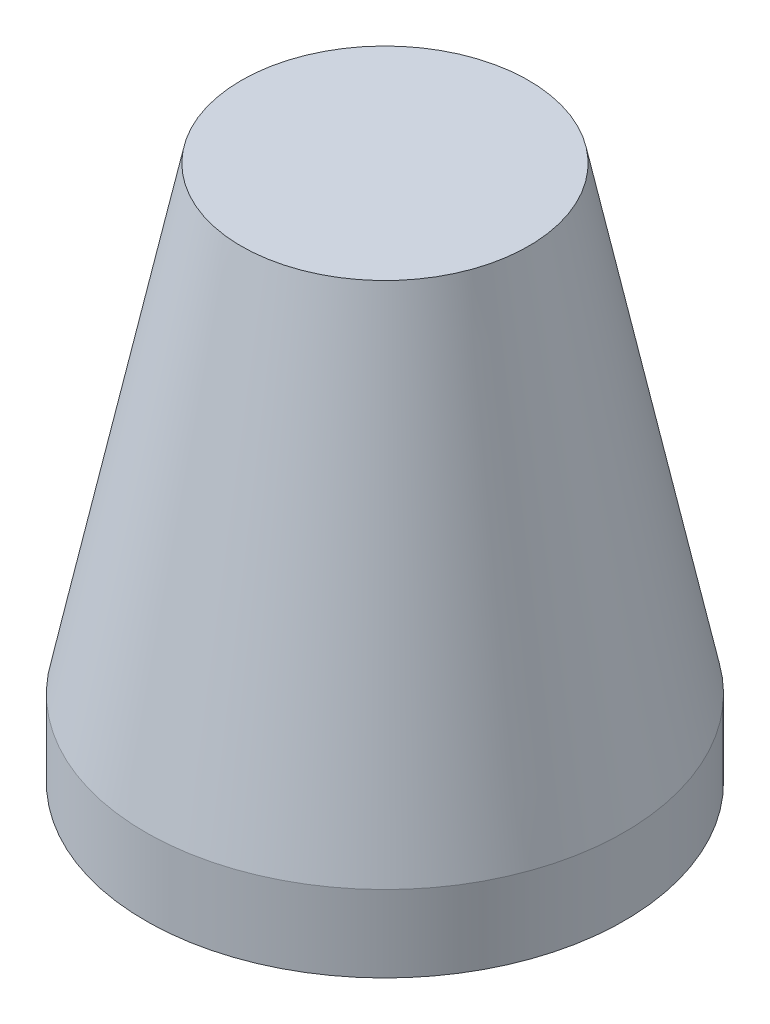
SolidWorks part; units mm, degrees
ref_plane "前视基准面" through (0, 0, 0) normal (0, 0, 1) x (1, 0, 0)
ref_plane "上视基准面" through (0, 0, 0) normal (0, 1, 0) x (1, 0, 0)
ref_plane "右视基准面" through (0, 0, 0) normal (1, 0, 0) x (0, 0, -1)
other "Configuration Table"
sketch "草图1" plane through (0, 0, 0) normal (0, 0, 1) x (1, 0, 0)
  line L0 (0, 56) -> (0, 0)
  line L1 (0, 0) -> (-25, 0)
  line L2 (-25, 0) -> (-25, 8)
  line L3 (-25, 8) -> (-15, 56)
  line L4 (-15, 56) -> (0, 56)
  dimension "D1" = 25
  dimension "D2" = 8
  dimension "D3" = 56
  dimension "D4" = 15
revolve "旋转1" add sketch "草图1" angle 360 about L0
